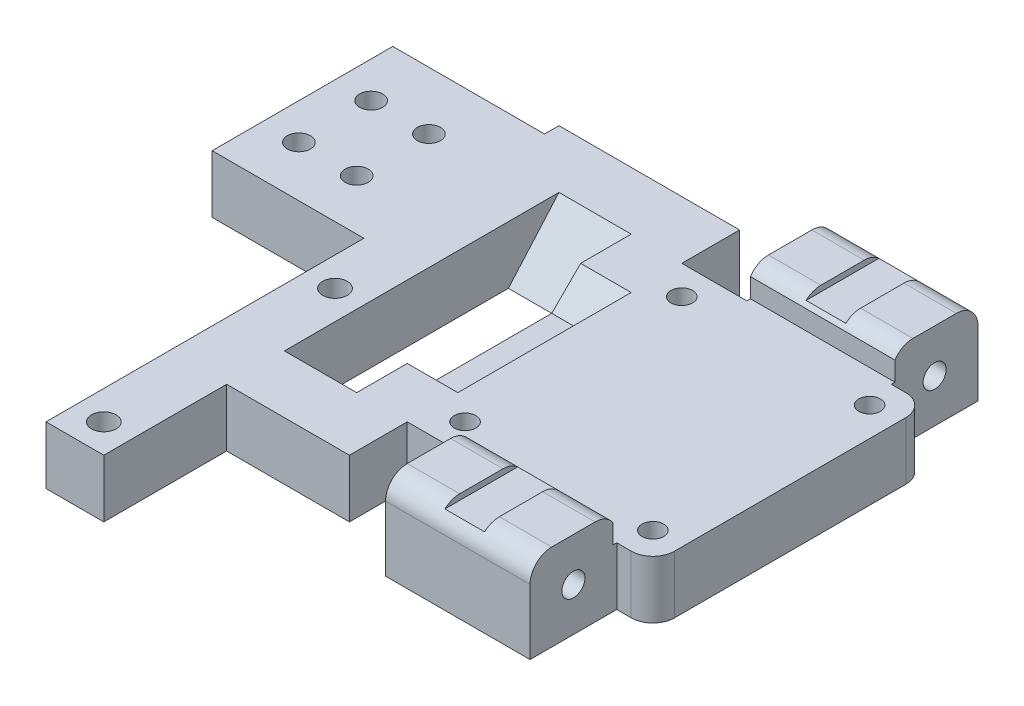
SolidWorks part; units mm, degrees
ref_plane "Front" through (0, 0, 0) normal (0, 0, 1) x (1, 0, 0)
ref_plane "Top" through (0, 0, 0) normal (0, 1, 0) x (1, 0, 0)
ref_plane "Right" through (0, 0, 0) normal (1, 0, 0) x (0, 0, -1)
sketch "Sketch1" plane through (0, 0, 0) normal (0, 1, 0) x (1, 0, 0)
  line L1 (0, 0) -> (300, 0)
  line L2 (0, 0) -> (0, -20)
  line L3 (0, -20) -> (300, -20)
  line L4 (300, 0) -> (300, -20)
  dimension "D1" = 20
  dimension "D2" = 300
extrude "Boss-Extrude1" add sketch "Sketch1" along normal blind 8
sketch "Sketch2" plane through (0, 0, 20) normal (0, 0, 1) x (1, 0, 0)
  line L0 (0, 8) -> (300, 8) construction
  line L1 (0, 0) -> (34, 0)
  line L2 (0, 0) -> (0, 8)
  line L3 (0, 8) -> (34, 8)
  line L4 (34, 0) -> (34, 8)
  line L5 (266, 8) -> (300, 8)
  line L6 (300, 0) -> (300, 8)
  line L7 (266, 0) -> (300, 0)
  line L8 (266, 0) -> (266, 8)
  dimension "D1" = 34
  dimension "D2" = 2
extrude "Boss-Extrude2" add sketch "Sketch2" along normal blind 9
sketch "Sketch3" plane through (0, 0, 0) normal (0, 0, -1) x (-1, 0, 0)
  line L0 (-300, 8) -> (0, 8) construction
  line L1 (0, 0) -> (-34, 0)
  line L2 (0, 0) -> (0, 8)
  line L3 (0, 8) -> (-34, 8)
  line L4 (-34, 0) -> (-34, 8)
  line L5 (-300, 0) -> (-300, 8)
  line L6 (-266, 8) -> (-300, 8)
  line L7 (-266, 0) -> (-266, 8)
  line L8 (-266, 0) -> (-300, 0)
  dimension "D1" = 34
  dimension "D2" = 2
extrude "Boss-Extrude3" add sketch "Sketch3" along normal blind 9
sketch "Sketch4" plane through (0, 8, 0) normal (0, 1, 0) x (1, 0, 0)
  line L0 (0, 9) -> (34, 9) construction
  line L1 (0, 9) -> (0, -29) construction
  circle A0 centre (4, 5) radius 1.5
  circle A1 centre (30, 5) radius 1.5
  circle A2 centre (30, -25) radius 1.5
  circle A3 centre (4, -25) radius 1.5
  circle A4 centre (296, -25) radius 1.5
  circle A5 centre (296, 5) radius 1.5
  circle A6 centre (270, -25) radius 1.5
  circle A7 centre (270, 5) radius 1.5
  dimension "D1" = 3
  dimension "D2" = 4
  dimension "D3" = 4
  dimension "D4" = 2
  dimension "D5" = 2
  dimension "D6" = 2
extrude "Cut-Extrude1" cut sketch "Sketch4" against normal through all
sketch "Sketch5" plane through (0, 0, 20) normal (0, 0, 1) x (1, 0, 0)
  line L0 (34, 8) -> (266, 8) construction
  line L1 (266, 0) -> (241, 0)
  line L2 (266, 0) -> (266, 8)
  line L3 (266, 8) -> (241, 8)
  line L4 (241, 0) -> (241, 8)
  dimension "D1" = 25
extrude "Boss-Extrude4" add sketch "Sketch5" along normal blind 17
sketch "Sketch6" plane through (0, 0, 0) normal (0, 0, -1) x (-1, 0, 0)
  line L0 (-266, 0) -> (-34, 0) construction
  line L1 (-266, 8) -> (-241, 8)
  line L2 (-266, 8) -> (-266, 0)
  line L3 (-266, 0) -> (-241, 0)
  line L4 (-241, 8) -> (-241, 0)
  dimension "D1" = 25
extrude "Boss-Extrude5" add sketch "Sketch6" along normal blind 17
sketch "Sketch7" plane through (0, 8, 0) normal (0, 1, 0) x (1, 0, 0)
  line L0 (266, -37) -> (241, -37) construction
  line L1 (259, -29) -> (249, -29)
  line L2 (259, -29) -> (259, 9)
  line L3 (259, 9) -> (249, 9)
  line L4 (249, -29) -> (249, 9)
  line L5 (241, -37) -> (241, -20) construction
  dimension "D1" = 10
  dimension "D2" = 38
  dimension "D3" = 8
  dimension "D4" = 8
extrude "Cut-Extrude2" cut sketch "Sketch7" against normal through all
sketch "Sketch8" plane through (0, 8, 0) normal (0, 1, 0) x (1, 0, 0)
  line L0 (259, -29) -> (259, 9) construction
  line L1 (259, -18) -> (266, -18)
  line L2 (259, -18) -> (259, -2)
  line L3 (259, -2) -> (266, -2)
  line L4 (266, -18) -> (266, -2)
  line L5 (266, -37) -> (241, -37) construction
  dimension "D1" = 7
  dimension "D2" = 16
  dimension "D3" = 19
extrude "Cut-Extrude3" cut sketch "Sketch8" against normal blind 4
sketch "Sketch9" plane through (259, 0, 0) normal (-1, 0, 0) x (0, 0, 1)
  line L0 (18, 4) -> (22, 8)
  line L1 (29, 8) -> (18, 8) construction
  line L2 (22, 8) -> (18, 8)
  line L3 (18, 8) -> (18, 4)
  line L4 (2, 4) -> (-2, 8)
  line L5 (2, 8) -> (-9, 8) construction
  line L6 (-2, 8) -> (2, 8)
  line L7 (2, 8) -> (2, 4)
  dimension "D1" = 4
  dimension "D2" = 4
extrude "Cut-Extrude4" cut sketch "Sketch9" against normal blind 7
sketch "Sketch10" plane through (259, 0, 0) normal (-1, 0, 0) x (0, 0, 1)
  line L0 (-9, 8) -> (-2, 0)
  line L1 (29, 0) -> (-9, 0) construction
  line L2 (-2, 0) -> (-9, 0)
  line L3 (-9, 0) -> (-9, 8)
  line L4 (29, 8) -> (22, 0)
  line L5 (22, 0) -> (29, 0)
  line L6 (29, 0) -> (29, 8)
  line L7 (-51.4523, 12.1971) -> (-51.8778, 12.5861)
  line M6 (-9, 8) -> (-9, 0)
  line M7 (-9, 0) -> (29, 0)
  line M8 (29, 0) -> (29, 8)
  dimension "D1" = 7
  dimension "D2" = 7
extrude "Boss-Extrude6" add sketch "Sketch10" along normal blind 10 contours L0 M6 M7 | L4 M8 M7
sketch "Sketch12" plane through (0, 0, 37) normal (0, 0, 1) x (1, 0, 0)
  line L0 (241, 0) -> (266, 0) construction
  line L1 (241, 8) -> (249, 8)
  line L2 (241, 8) -> (241, 0)
  line L3 (241, 0) -> (249, 0)
  line L4 (249, 8) -> (249, 0)
  dimension "D1" = 8
extrude "Boss-Extrude7" add sketch "Sketch12" along normal blind 17
sketch "Sketch13" plane through (0, 8, 0) normal (0, 1, 0) x (1, 0, 0)
  line L0 (249, -54) -> (241, -54) construction
  line L1 (249, -54) -> (249, -37) construction
  circle A0 centre (245, -50) radius 1.7
  circle A1 centre (245, -18) radius 1.7
  dimension "D1" = 3.4
  dimension "D2" = 4
  dimension "D3" = 4
  dimension "D4" = 2
extrude "Cut-Extrude6" cut sketch "Sketch13" against normal through all
sketch "Sketch14" plane through (0, 0, 29) normal (0, 0, 1) x (1, 0, 0)
  line L1 (295, 12) -> (275, 12)
  line L2 (295, 12) -> (295, 0)
  line L3 (295, 0) -> (275, 0)
  line L4 (275, 12) -> (275, 0)
  line L5 (266, 0) -> (300, 0) construction
  line L7 (266, 8) -> (266, 0) construction
  dimension "D1" = 20
  dimension "D2" = 9
  dimension "D3" = 12
extrude "Boss-Extrude8" add sketch "Sketch14" along normal blind 12
sketch "Sketch15" plane through (295, 0, 0) normal (1, 0, 0) x (0, 0, -1)
  line L0 (-41, 0) -> (-41, 12) construction
  line L1 (-41, 12) -> (-29, 12) construction
  circle A0 centre (-35, 6) radius 1.6
  dimension "D1" = 3.2
  dimension "D2" = 6
  dimension "D3" = 6
extrude "Cut-Extrude7" cut sketch "Sketch15" against normal blind 20
sketch "Sketch16" plane through (0, 0, -9) normal (0, 0, -1) x (-1, 0, 0)
  line L1 (-295, 12) -> (-275, 12)
  line L2 (-295, 12) -> (-295, 0)
  line L3 (-295, 0) -> (-275, 0)
  line L4 (-275, 12) -> (-275, 0)
  line L5 (-300, 0) -> (-266, 0) construction
  line L6 (-266, 0) -> (-266, 8) construction
  dimension "D1" = 20
  dimension "D2" = 9
  dimension "D3" = 12
extrude "Boss-Extrude9" add sketch "Sketch16" along normal blind 12
sketch "Sketch17" plane through (295, 0, 0) normal (1, 0, 0) x (0, 0, -1)
  line L1 (21, 12) -> (21, 0) construction
  line L2 (21, 12) -> (9, 12) construction
  circle A0 centre (15, 6) radius 1.6
  dimension "D1" = 3.2
  dimension "D2" = 6
  dimension "D3" = 6
extrude "Cut-Extrude8" cut sketch "Sketch17" against normal blind 20
sketch "Sketch18" plane through (0, 0, -9) normal (0, 0, -1) x (-1, 0, 0)
  line L1 (-25, 13) -> (-5, 13)
  line L2 (-25, 13) -> (-25, 0)
  line L3 (-25, 0) -> (-5, 0)
  line L4 (-5, 13) -> (-5, 0)
  line L5 (-34, 0) -> (0, 0) construction
  line L6 (-34, 8) -> (-34, 0) construction
  dimension "D1" = 20
  dimension "D2" = 9
  dimension "D3" = 13
extrude "Boss-Extrude10" add sketch "Sketch18" along normal blind 12
sketch "Sketch19" plane through (5, 0, 0) normal (-1, 0, 0) x (0, 0, 1)
  line L0 (-21, 0) -> (-21, 13) construction
  line L1 (-21, 13) -> (-9, 13) construction
  circle A0 centre (-15, 8) radius 1.6
  dimension "D1" = 3.2
  dimension "D2" = 6
  dimension "D3" = 5
extrude "Cut-Extrude9" cut sketch "Sketch19" against normal blind 20
sketch "Sketch20" plane through (0, 0, 29) normal (0, 0, 1) x (1, 0, 0)
  line L1 (5, 13) -> (25, 13)
  line L2 (5, 13) -> (5, 0)
  line L3 (5, 0) -> (25, 0)
  line L4 (25, 13) -> (25, 0)
  line L5 (0, 0) -> (34, 0) construction
  line L6 (34, 0) -> (34, 8) construction
  dimension "D1" = 20
  dimension "D2" = 9
  dimension "D3" = 13
extrude "Boss-Extrude11" add sketch "Sketch20" along normal blind 12
sketch "Sketch21" plane through (5, 0, 0) normal (-1, 0, 0) x (0, 0, 1)
  line L0 (41, 13) -> (41, 0) construction
  line L2 (41, 13) -> (29, 13) construction
  circle A0 centre (35, 8) radius 1.6
  dimension "D1" = 3.2
  dimension "D2" = 6
  dimension "D3" = 5
extrude "Cut-Extrude10" cut sketch "Sketch21" against normal blind 20
fillet "Fillet6" radius 3 8 edges at (15, 13, 41) (15, 13, 29) (15, 13, -9) (15, 13, -21) (285, 12, 41) (285, 12, 29) (285, 12, -9) (285, 12, -21)
sketch "Sketch28" plane through (0, 0, 0) normal (-1, 0, 0) x (0, 0, 1)
  line L1 (78.9453, 217.6934) -> (-119.9362, 217.6934)
  line L2 (78.9453, 217.6934) -> (78.9453, -338.6618)
  line L3 (78.9453, -338.6618) -> (-119.9362, -338.6618)
  line L4 (-119.9362, 217.6934) -> (-119.9362, -338.6618)
extrude "Cut-Extrude14" cut sketch "Sketch28" against normal blind 220
sketch "Sketch29" plane through (0, 0, 0) normal (0, 0, -1) x (-1, 0, 0)
  line L1 (-241, 0) -> (-220, 0)
  line L2 (-241, 0) -> (-241, 8)
  line L3 (-241, 8) -> (-220, 8)
  line L4 (-220, 0) -> (-220, 8)
extrude "Boss-Extrude12" add sketch "Sketch29" along normal blind 15
sketch "Sketch30" plane through (0, 0, 0) normal (0, -1, 0) x (-1, 0, 0)
  line L1 (-220, -20) -> (-241, -20)
  line L2 (-220, -20) -> (-220, -10)
  line L3 (-220, -10) -> (-241, -10)
  line L4 (-241, -20) -> (-241, -10)
  dimension "D1" = 21
  dimension "D2" = 10
extrude "Cut-Extrude15" cut sketch "Sketch30" against normal through all
sketch "Sketch31" plane through (0, 0, 0) normal (0, -1, 0) x (-1, 0, 0)
  line L0 (-220, -10) -> (-220, 15) construction
  line L1 (-241, 15) -> (-220, 15) construction
  line L2 (-220, -10) -> (-241, -10) construction
  circle A0 centre (-225, 7) radius 1.6
  circle A1 centre (-225, -3) radius 1.6
  circle A2 centre (-233, 7) radius 1.6
  circle A3 centre (-233, -3) radius 1.6
  dimension "D1" = 3.2
  dimension "D2" = 3.2
  dimension "D3" = 3.2
  dimension "D4" = 3.2
  dimension "D5" = 5
  dimension "D6" = 8
  dimension "D7" = 5
  dimension "D8" = 7
  dimension "D9" = 8
  dimension "D10" = 8
  dimension "D11" = 7
  dimension "D12" = 8
extrude "Cut-Extrude16" cut sketch "Sketch31" against normal through all
fillet "Fillet7" radius 3 2 edges at (300, 4, -9) (300, 4, 29)
sketch "Sketch32" plane through (0, 12, 0) normal (0, 1, 0) x (1, 0, 0)
  line L0 (295, -38) -> (295, -32) construction
  line L1 (287.75, -42.4531) -> (282.25, -42.4531)
  line L2 (287.75, -42.4531) -> (287.75, 28.0104)
  line L3 (287.75, 28.0104) -> (282.25, 28.0104)
  line L4 (282.25, -42.4531) -> (282.25, 28.0104)
  dimension "D1" = 5.5
  dimension "D2" = 7.25
extrude "Cut-Extrude17" cut sketch "Sketch32" against normal blind 0.8
sketch "Sketch33" plane through (0, 0, 29) normal (0, 0, -1) x (-1, 0, 0)
  line L1 (-275, 8) -> (-295, 8)
  line L2 (-275, 8) -> (-275, 12.9638)
  line L3 (-275, 12.9638) -> (-295, 12.9638)
  line L4 (-295, 8) -> (-295, 12.9638)
  dimension "D1" = 20
extrude "Cut-Extrude18" cut sketch "Sketch33" against normal blind 0.5
sketch "Sketch34" plane through (0, 0, -9) normal (0, 0, 1) x (1, 0, 0)
  line L1 (275, 8) -> (295, 8)
  line L2 (275, 8) -> (275, 19.9424)
  line L3 (275, 19.9424) -> (295, 19.9424)
  line L4 (295, 8) -> (295, 19.9424)
  dimension "D1" = 20
extrude "Cut-Extrude19" cut sketch "Sketch34" against normal blind 0.5
